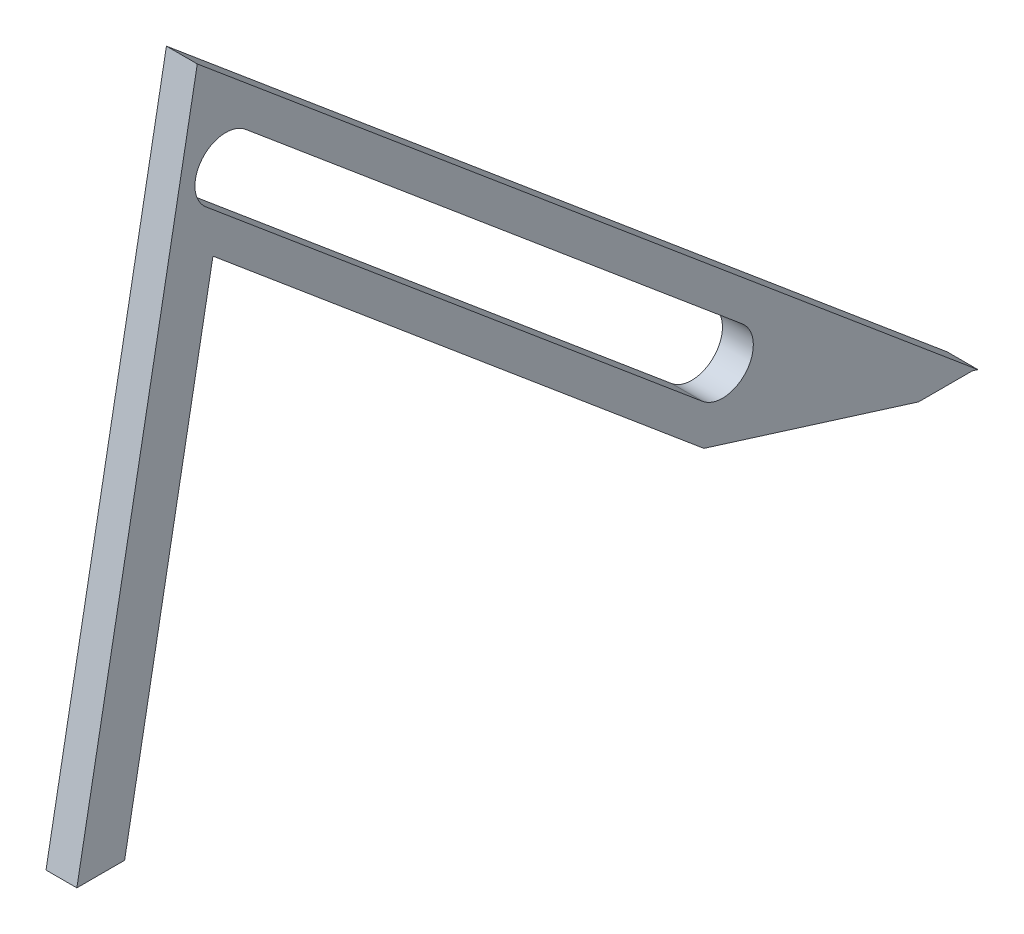
SolidWorks part; units mm, degrees
ref_plane "Front Plane" through (0, 0, 0) normal (0, 0, 1) x (1, 0, 0)
ref_plane "Top Plane" through (0, 0, 0) normal (0, 1, 0) x (1, 0, 0)
ref_plane "Right Plane" through (0, 0, 0) normal (1, 0, 0) x (0, 0, -1)
sketch "Sketch1" plane through (0, 0, 0) normal (1, 0, 0) x (0, 0, -1)
  line L0 (-444.5, 0) -> (444.5, 0) construction
  line L1 (-444.5, 0) -> (-394.9465, 268.859) construction
  line L2 (-394.9465, 268.859) -> (-444.5, 0)
  line L3 (-394.9465, 268.859) -> (-73.6751, -0.7197)
  line L4 (-394.9465, 268.859) -> (-394.9465, 0) construction
  line L9 (-73.6751, -0.7197) -> (-75.9791, 0)
  line L10 (-234.3108, 134.0696) -> (-284.8519, 73.8371) construction
  line L16 (-284.8519, 73.8371) -> (-411.8843, 180.4299) construction
  line L17 (-284.8519, 73.8371) -> (-94.5385, -85.8549) construction
  line L18 (-394.9465, 0) -> (-394.9465, -231.14) construction
  line L19 (-242.4742, 124.3409) -> (-318.8422, 188.4213) construction
  line L20 (-258.801, 104.8834) -> (-352.5253, 183.5274) construction
  line L21 (-266.9644, 95.1546) -> (-388.5086, 197.1423)
  line L22 (-266.9644, 95.1546) -> (-186.4616, 27.6047)
  line L23 (-419.7233, 134.4295) -> (-381.7028, 127.4219) construction
  line L24 (-400.713, 130.9257) -> (-424.844, 0) construction
  line L25 (-400.713, 130.9257) -> (-388.5086, 197.1423) construction
  line L26 (-388.5086, 197.1423) -> (-424.844, 0)
  line L27 (-98.0924, 0) -> (-186.4616, 27.6047)
  line L28 (-326.5453, 194.8849) -> (-342.8721, 175.4274) construction
  line L29 (-334.7087, 185.1562) -> (-383.2159, 225.8585) construction
  line L30 (-334.7087, 185.1562) -> (-178.8305, 54.3588) construction
  line L31 (-383.2159, 225.8585) -> (-178.8305, 54.3588) construction
  line L32 (-375.0525, 235.5873) -> (-170.6671, 64.0876)
  line L33 (-391.3793, 216.1298) -> (-186.9939, 44.63)
  line L34 (-444.5, 0) -> (-424.844, 0)
  line L35 (-98.0924, 0) -> (-75.9791, 0)
  line L36 (-385.8623, 211.5004) -> (-377.9232, 254.5748) construction
  arc A2 (-375.0525, 235.5873) -> (-391.3793, 216.1298) centre (-383.2159, 225.8585) ccw
  arc A3 (-186.9939, 44.63) -> (-170.6671, 64.0876) centre (-178.8305, 54.3588) ccw
  point P4 (0, 0)
  point P32 (-281.0232, 140.1087)
  dimension "D1" = 889
  dimension "D7" = 12.7
  dimension "D2" = 231.14
  dimension "D3" = 499.999
  dimension "D4" = 25.4
  dimension "D5" = 12.7
  dimension "D6" = 12.7
  dimension "D8" = 19.656
  dimension "D9" = 22.1133
  dimension "D10" = 40
extrude "Boss-Extrude1" add sketch "Sketch1" along normal blind 12.7
